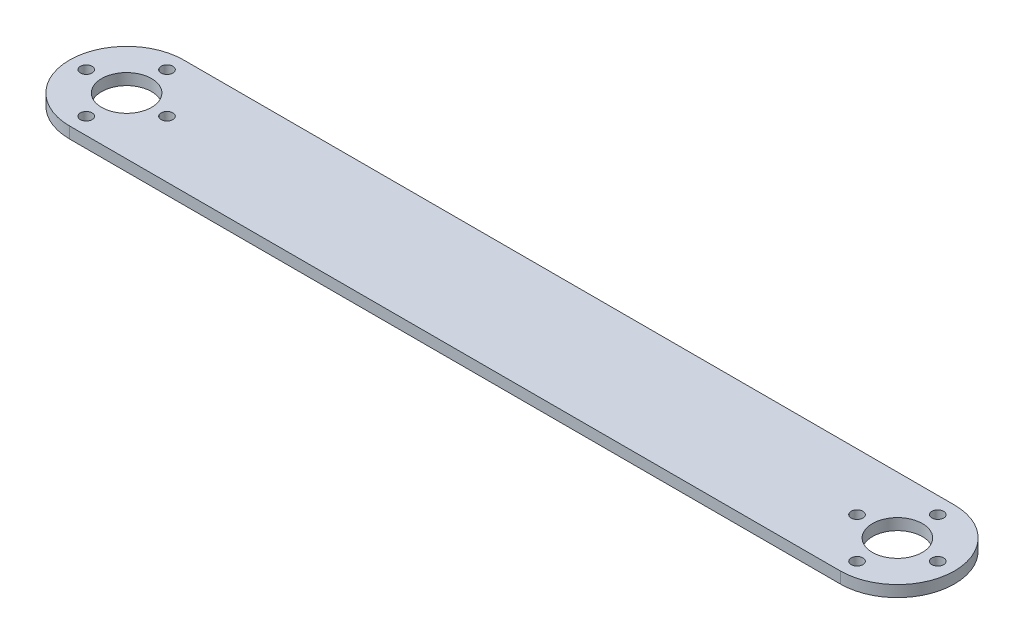
SolidWorks part; units mm, degrees
ref_plane "Front" through (0, 0, 0) normal (0, 0, 1) x (1, 0, 0)
ref_plane "Top" through (0, 0, 0) normal (0, 1, 0) x (1, 0, 0)
ref_plane "Right" through (0, 0, 0) normal (1, 0, 0) x (0, 0, -1)
sketch "Sketch1" plane through (0, 0, 0) normal (0, 1, 0) x (1, 0, 0)
  line L1 (0, 0) -> (216, 0)
  line L2 (0, 0) -> (0, 32)
  line L3 (0, 32) -> (216, 32)
  line L4 (216, 0) -> (216, 32)
  arc A0 (0, 32) -> (0, 0) centre (0, 16) ccw
  arc A1 (216, 32) -> (216, 0) centre (216, 16) cw
  circle A2 centre (0, 16) radius 7
  circle A3 centre (216, 16) radius 7
  dimension "D1" = 32
  dimension "D2" = 216
extrude "Boss-Extrude1" add sketch "Sketch1" along normal blind 3.175 contours A3 L4 L3 L2 A2 L1 | A2 L2 A0 | A3 L4 A1
sketch "Sketch2" plane through (0, 3.175, 0) normal (0, 1, 0) x (1, 0, 0)
  line L0 (108, 32) -> (108, 0)
  line L1 (0, 32) -> (216, 32) construction
  line L2 (0, 0) -> (216, 0) construction
  circle A0 centre (0, 16) radius 11.3137
  circle A1 centre (-11.3137, 16) radius 1.65
  circle A2 centre (11.3137, 16) radius 1.65
  circle A3 centre (0, 27.3137) radius 1.65
  circle A4 centre (0, 4.6863) radius 1.65
  circle A5 centre (216, 4.6863) radius 1.65
  circle A6 centre (204.6863, 16) radius 1.65
  circle A7 centre (227.3137, 16) radius 1.65
  circle A8 centre (216, 27.3137) radius 1.65
extrude "Cut-Extrude1" cut sketch "Sketch2" against normal blind 10 contours A6 | A8 | A1 | A3 | A2 | A4 | A5 | A7
